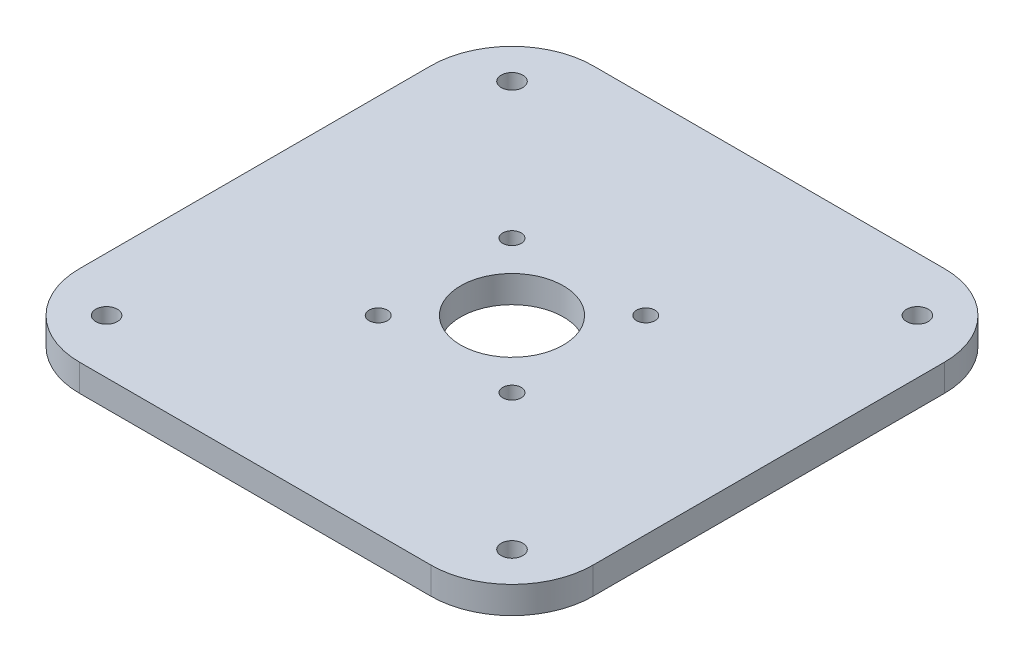
SolidWorks part; units mm, degrees
ref_plane "前视基准面" through (0, 0, 0) normal (0, 0, 1) x (1, 0, 0)
ref_plane "上视基准面" through (0, 0, 0) normal (0, 1, 0) x (1, 0, 0)
ref_plane "右视基准面" through (0, 0, 0) normal (1, 0, 0) x (0, 0, -1)
sketch "Sketch2" plane through (0, 0, 0) normal (0, 1, 0) x (1, 0, 0)
  line L1 (95, -95) -> (-95, -95)
  line L2 (95, -95) -> (95, 95)
  line L3 (95, 95) -> (-95, 95)
  line L4 (-95, -95) -> (-95, 95)
  line L5 (95, -95) -> (-95, 95) construction
  line L6 (95, 95) -> (-95, -95) construction
  point P0 (0, 0)
  dimension "D1" = 190
  dimension "D2" = 190
extrude "Extrude1" add sketch "Sketch2" along normal blind 10
sketch "Sketch3" plane through (0, 10, 0) normal (0, 1, 0) x (1, 0, 0)
  line L0 (0, 75) -> (0, -75) construction
  line L1 (75, -75) -> (-75, -75) construction
  line L2 (75, -75) -> (75, 75) construction
  line L3 (75, 75) -> (-75, 75) construction
  line L4 (-75, -75) -> (-75, 75) construction
  line L5 (75, -75) -> (-75, 75) construction
  line L6 (75, 75) -> (-75, -75) construction
  line L7 (-75, 0) -> (75, 0) construction
  circle A0 centre (0, 0) radius 19
  circle A1 centre (-75, 75) radius 4
  circle A2 centre (75, 75) radius 4
  circle A3 centre (75, -75) radius 4
  circle A4 centre (-75, -75) radius 4
  dimension "D3" = 8
  dimension "D4" = 38
  dimension "D1" = 150
  dimension "D2" = 150
extrude "Extrude2" cut sketch "Sketch3" against normal blind 10
fillet "Fillet1" radius 30 4 edges at (-95, 5, 95) (95, 5, 95) (95, 5, -95) (-95, 5, -95)
sketch "Sketch4" plane through (0, 10, 0) normal (0, 1, 0) x (1, 0, 0)
  line L1 (24.7487, -24.7487) -> (-24.7487, -24.7487) construction
  line L2 (24.7487, -24.7487) -> (24.7487, 24.7487) construction
  line L3 (24.7487, 24.7487) -> (-24.7487, 24.7487) construction
  line L4 (-24.7487, -24.7487) -> (-24.7487, 24.7487) construction
  line L5 (24.7487, -24.7487) -> (-24.7487, 24.7487) construction
  line L6 (24.7487, 24.7487) -> (-24.7487, -24.7487) construction
  circle A0 centre (0, 0) radius 35 construction
  dimension "D1" = 70
hole_wizard "M8 Tapped Hole1" positions "3DSketch1" profile "Sketch5" tap size "M8" standard "GB"
sketch3d "3DSketch1"
  point P0 (-24.7487, 10, -24.7487)
  point P3 (24.7487, 10, -24.7487)
  point P6 (-24.7487, 10, 24.7487)
  point P9 (24.7487, 10, 24.7487)
sketch "Sketch5" plane through (-24.7487, 10, -24.7487) normal (1, 0, 0) x (0, 0, 1)
  line L0 (0, 0) -> (0, 21.7929)
  line L1 (0, 21.7929) -> (3.4, 19.75)
  line L2 (3.4, 19.75) -> (3.4, 0)
  line L5 (3.4, 0) -> (0, 0)
  line L10 (0, 21.7929) -> (-3.4, 19.75) construction
  line L11 (0, -6.35) -> (0, 107.95) construction
  dimension "螺纹孔钻头直径" = 6.8
  dimension "螺纹孔钻头深度" = 19.75
  dimension "导头角度" = 118
